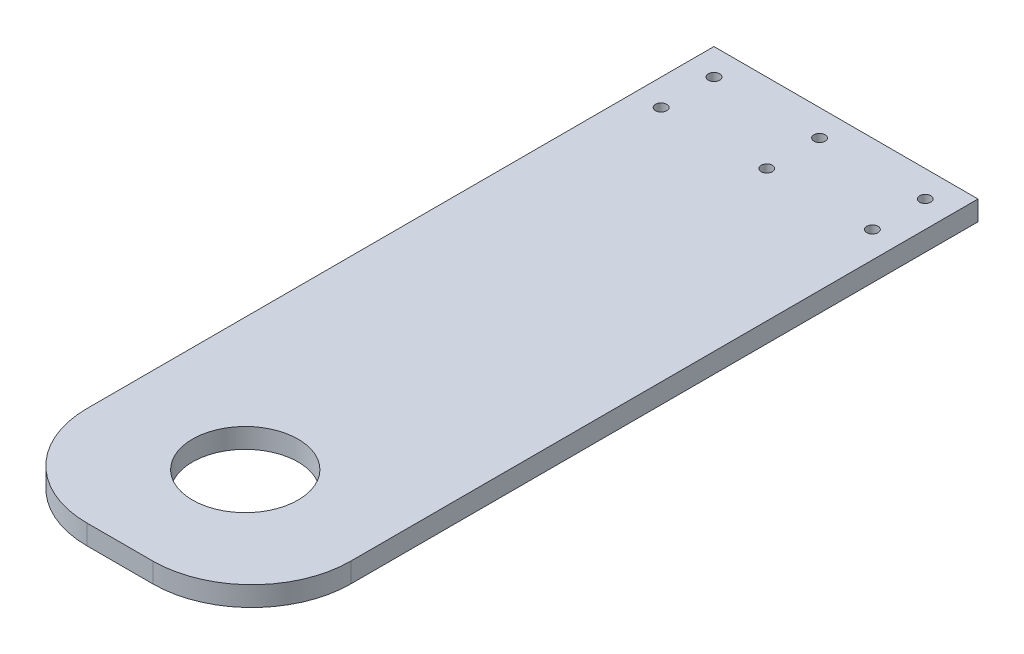
SolidWorks part; units mm, degrees
material "6061-T6 (SS)"
ref_plane "Front Plane" through (0, 0, 0) normal (0, 0, 1) x (1, 0, 0)
ref_plane "Top Plane" through (0, 0, 0) normal (0, 1, 0) x (1, 0, 0)
ref_plane "Right Plane" through (0, 0, 0) normal (1, 0, 0) x (0, 0, -1)
sketch "Sketch1" plane through (0, 0, 0) normal (0, 1, 0) x (1, 0, 0)
  line L1 (0, 0) -> (80, 0)
  line L2 (0, 0) -> (0, -230)
  line L3 (0, -230) -> (80, -230)
  line L4 (80, 0) -> (80, -230)
  dimension "D1" = 80
  dimension "D2" = 230
extrude "Boss-Extrude1" add sketch "Sketch1" along normal blind 6
sketch "Sketch5" plane through (0, 6, 0) normal (0, 1, 0) x (1, 0, 0)
  circle A1 centre (40, -192) radius 20
  circle A2 centre (40, -192) radius 48.5 construction
  point P1 (40, -192)
hole_wizard "Ø32.0 (32) Diameter Hole1" positions "Sketch5" profile "Sketch6" hole size "Ø32.0" standard "DIN" end condition through all
sketch "Sketch6" plane through (40, 6, 192) normal (1, 0, 0) x (0, 0, 1)
  line L0 (0, 0) -> (0, 6)
  line L1 (0, 6) -> (16, 6)
  line L2 (16, 6) -> (16, 0)
  line L5 (16, 0) -> (0, 0)
  line L11 (0, -6.35) -> (0, 107.95) construction
  dimension "Thru Hole Dia." = 32
  dimension "Thru Hole Depth" = 6
fillet "Fillet1" radius 30 2 edges at (0, 3, 230) (80, 3, 230)
sketch "Sketch9" plane through (0, 0, 0) normal (0, 1, 0) x (1, 0, 0)
  line L0 (40, 0) -> (40, -57.4233) construction
  line L1 (80, 0) -> (0, 0) construction
  point P0 (8, -18)
  point P6 (40, -18)
  point P7 (72, -18)
  point P8 (40, -34)
  point P9 (72, -34)
  point P10 (8, -34)
  dimension "D3" = 18
  dimension "D1" = 3
  dimension "D2" = 2
hole_wizard "CBORE for M3 Hex Socket Head Cap Screw1" positions "Sketch9" profile "Sketch8" counterbore size "M3" standard "DIN" end condition through all
sketch "Sketch8" plane through (8, 0, 18) normal (1, 0, 0) x (0, 0, -1)
  line L0 (0, 0) -> (0, 6)
  line L1 (0, 6) -> (1.7, 6)
  line L3 (1.7, 6) -> (1.7, 3.4)
  line L4 (1.7, 3.4) -> (3.25, 3.4)
  line L5 (3.25, 3.4) -> (3.25, 0)
  line L7 (3.25, 0) -> (0, 0)
  line L11 (0, -6.35) -> (0, 107.95) construction
  dimension "Thru Hole Dia." = 3.4
  dimension "Thru Hole Depth" = 6
  dimension "C'Bore Dia." = 6.5
  dimension "C'Bore Depth" = 3.4
sketch "Sketch10" plane through (0, 6, 0) normal (0, 1, 0) x (1, 0, 0)
  line L0 (80, -200) -> (80, 0) construction
  line L1 (0, 0) -> (80, 0)
  line L2 (0, 0) -> (0, -10)
  line L3 (0, -10) -> (80, -10)
  line L4 (80, 0) -> (80, -10)
  dimension "D1" = 10
extrude "Cut-Extrude1" cut sketch "Sketch10" against normal through all
